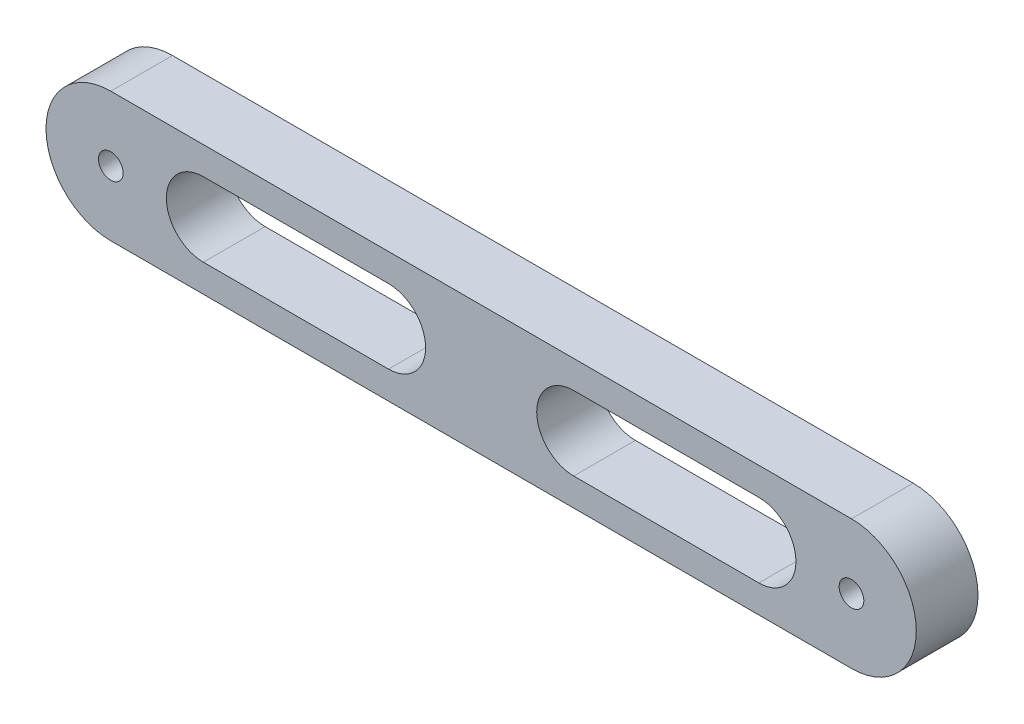
SolidWorks part; units mm, degrees
ref_plane "前视基准面" through (0, 0, 0) normal (0, 0, 1) x (1, 0, 0)
ref_plane "上视基准面" through (0, 0, 0) normal (0, 1, 0) x (1, 0, 0)
ref_plane "右视基准面" through (0, 0, 0) normal (1, 0, 0) x (0, 0, -1)
other "Configuration Table"
sketch "草图1" plane through (0, 0, 0) normal (0, 0, 1) x (1, 0, 0)
  line L0 (0, 0) -> (600, 0) construction
  line L1 (0, 52.5) -> (600, 52.5)
  line L2 (0, -52.5) -> (600, -52.5)
  arc A0 (0, 52.5) -> (0, -52.5) centre (0, 0) ccw
  arc A1 (600, -52.5) -> (600, 52.5) centre (600, 0) ccw
  point P3 (300, 0)
  dimension "D1" = 600
  dimension "D2" = 105
extrude "凸台-拉伸1" add sketch "草图1" along normal blind 50
sketch "草图2" plane through (0, 0, 50) normal (0, 0, 1) x (1, 0, 0)
  line L0 (0, 0) -> (434.8893, 0) construction
  line L1 (75, 0) -> (225, 0) construction
  line L2 (75, 30) -> (225, 30)
  line L3 (75, -30) -> (225, -30)
  line L4 (375, 0) -> (525, 0) construction
  line L5 (375, 30) -> (525, 30)
  line L6 (375, -30) -> (525, -30)
  line L7 (300, -52.5) -> (300, 52.5) construction
  line L8 (0, -52.5) -> (600, -52.5) construction
  line L9 (600, 52.5) -> (0, 52.5) construction
  circle A0 centre (0, 0) radius 10
  circle A1 centre (600, 0) radius 10
  arc A2 (75, 30) -> (75, -30) centre (75, 0) ccw
  arc A3 (225, -30) -> (225, 30) centre (225, 0) ccw
  arc A4 (375, 30) -> (375, -30) centre (375, 0) ccw
  arc A5 (525, -30) -> (525, 30) centre (525, 0) ccw
  point P10 (150, 0)
  point P15 (450, 0)
  dimension "D1" = 20
  dimension "D2" = 20
  dimension "D3" = 150
  dimension "D4" = 150
  dimension "D5" = 150
  dimension "D6" = 75
  dimension "D7" = 60
  dimension "D8" = 60
extrude "切除-拉伸1" cut sketch "草图2" against normal through all contours L6 A5 L5 A4 | A1 | A0 | L3 A3 L2 A2
